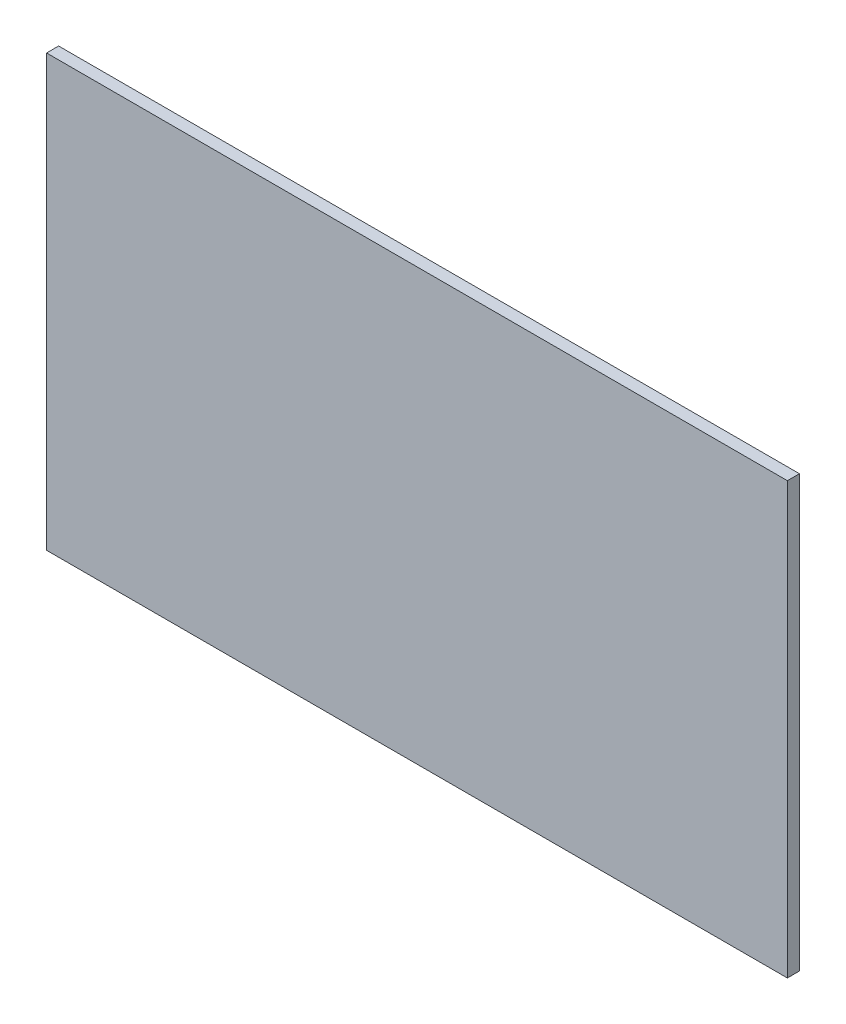
SolidWorks part; units mm, degrees
ref_plane "Plan de face" through (0, 0, 0) normal (0, 0, 1) x (1, 0, 0)
ref_plane "Plan de dessus" through (0, 0, 0) normal (0, 1, 0) x (1, 0, 0)
ref_plane "Plan de droite" through (0, 0, 0) normal (1, 0, 0) x (0, 0, -1)
sketch "Esquisse1" plane through (0, 0, 0) normal (0, 0, 1) x (1, 0, 0)
  line L1 (-105.4717, 81.5471) -> (152.5283, 81.5471)
  line L2 (-105.4717, 81.5471) -> (-105.4717, -68.4529)
  line L3 (-105.4717, -68.4529) -> (152.5283, -68.4529)
  line L4 (152.5283, 81.5471) -> (152.5283, -68.4529)
  dimension "D1" = 258
  dimension "D2" = 150
extrude "Boss.-Extru.1" add sketch "Esquisse1" along normal blind 4.2
